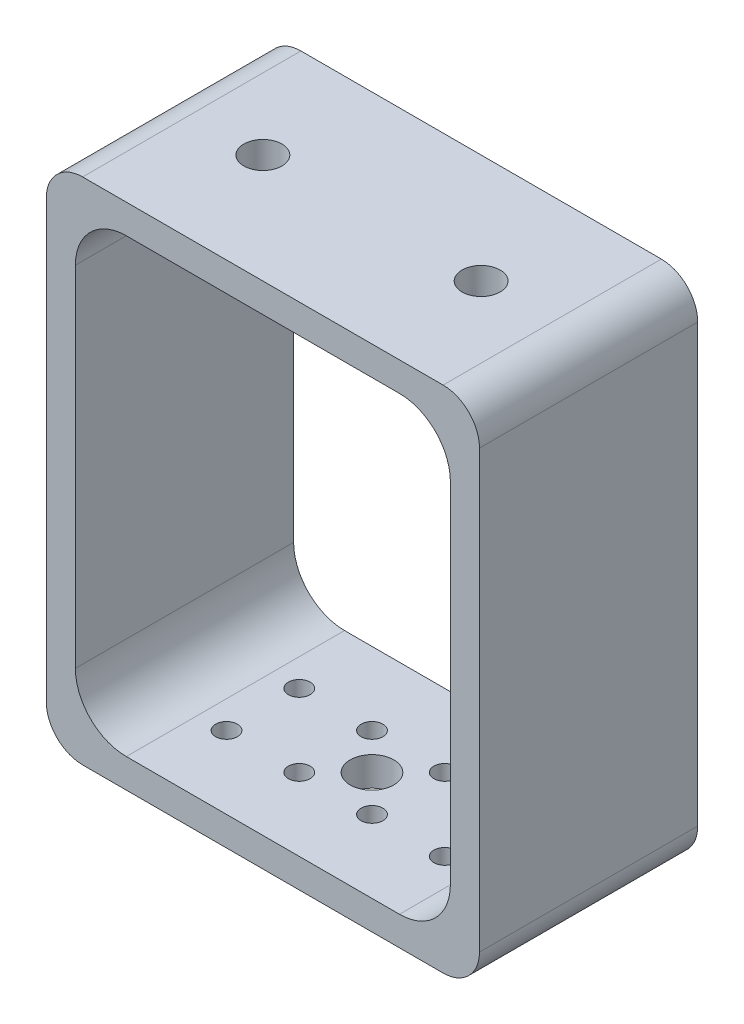
SolidWorks part; units mm, degrees
ref_plane "前视基准面" through (0, 0, 0) normal (0, 0, 1) x (1, 0, 0)
ref_plane "上视基准面" through (0, 0, 0) normal (0, 1, 0) x (1, 0, 0)
ref_plane "右视基准面" through (0, 0, 0) normal (1, 0, 0) x (0, 0, -1)
sketch "草图1" plane through (0, 0, 0) normal (0, 0, 1) x (1, 0, 0)
  line L0 (0, 0) -> (0, 113.274) construction
  line L1 (0, -133.973) -> (0, 133.973) construction
  line L2 (29.774, 0) -> (29.774, 70)
  line L3 (-29.774, 0) -> (29.774, 0)
  line L4 (29.774, 70) -> (0, 70)
  line L6 (-29.774, 70) -> (0, 70)
  line L7 (-29.774, 0) -> (-29.774, 70)
  dimension "D1" = 70
extrude "拉伸-薄壁2" add sketch "草图1" along normal mid plane 30 thin thin type one direction reverse wall 4
sketch "草图2" plane through (0, 66, 0) normal (0, -1, 0) x (-1, 0, 0)
  circle A0 centre (-15, 0) radius 2.6207
  circle A1 centre (0, 0) radius 15 construction
  circle A2 centre (15, 0) radius 2.6207
  point P10 (0, 0)
  dimension "D1" = 2
extrude "切除-拉伸1" cut sketch "草图2" against normal through all
fillet "圆角1" radius 7 4 edges at (25.774, 4, 0) (-25.774, 4, 0) (25.774, 66, 0) (-25.774, 66, 0)
sketch "草图3" plane through (0, 0, 0) normal (0, 1, 0) x (1, 0, 0)
  line L0 (-37.276, 0) -> (37.1787, 0) construction
  line L1 (0, 20.7792) -> (0, -20.3899) construction
  circle A0 centre (0, 0) radius 3
  circle A1 centre (-15, 5) radius 1.5
  circle A2 centre (-5, 5) radius 1.5
  circle A3 centre (5, 5) radius 1.5
  circle A4 centre (15, 5) radius 1.5
  circle A5 centre (-5, -5) radius 1.5
  circle A6 centre (5, -5) radius 1.5
  circle A7 centre (15, -5) radius 1.5
  circle A8 centre (-15, -5) radius 1.5
  dimension "D1" = 6
  dimension "D2" = 3
  dimension "D3" = 15
  dimension "D4" = 5
  dimension "D5" = 4
  dimension "D6" = 2
extrude "切除-拉伸2" cut sketch "草图3" along normal up to next
fillet "圆角2" radius 5 4 edges at (-29.774, 0, 0) (29.774, 0, 0) (29.774, 70, 0) (-29.774, 70, 0)
